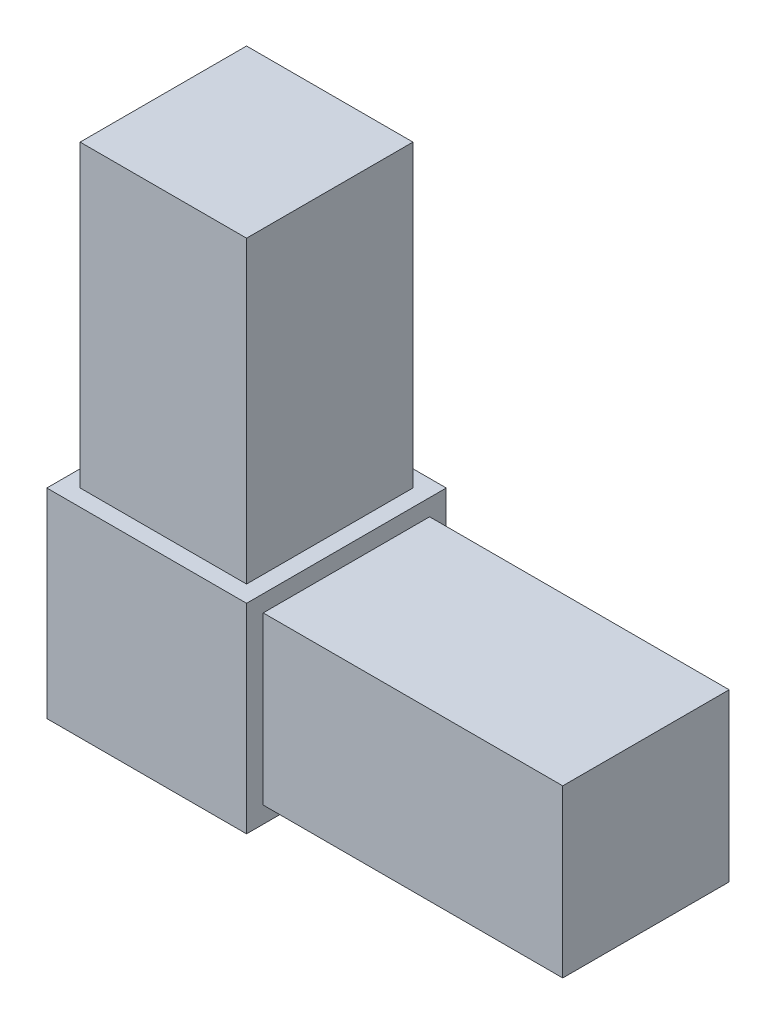
SolidWorks part; units mm, degrees
material "ABS"
ref_plane "Front Plane" through (0, 0, 0) normal (0, 0, 1) x (1, 0, 0)
ref_plane "Top Plane" through (0, 0, 0) normal (0, 1, 0) x (1, 0, 0)
ref_plane "Right Plane" through (0, 0, 0) normal (1, 0, 0) x (0, 0, -1)
sketch "Sketch1" plane through (0, 0, 0) normal (0, 0, 1) x (1, 0, 0)
  line L1 (9.525, -9.525) -> (-9.525, -9.525)
  line L2 (9.525, -9.525) -> (9.525, 9.525)
  line L3 (9.525, 9.525) -> (-9.525, 9.525)
  line L4 (-9.525, -9.525) -> (-9.525, 9.525)
  line L5 (9.525, -9.525) -> (-9.525, 9.525) construction
  line L6 (9.525, 9.525) -> (-9.525, -9.525) construction
  point P0 (0, 0)
  dimension "D1" = 19.05
extrude "Boss-Extrude1" add sketch "Sketch1" along normal blind 19.05
sketch "Sketch2" plane through (0, 9.525, 0) normal (0, 1, 0) x (1, 0, 0)
  line L0 (-9.525, 0) -> (9.525, -19.05) construction
  line L2 (-7.9375, -1.5875) -> (7.9375, -1.5875)
  line L3 (-7.9375, -1.5875) -> (-7.9375, -17.4625)
  line L4 (-7.9375, -17.4625) -> (7.9375, -17.4625)
  line L5 (7.9375, -1.5875) -> (7.9375, -17.4625)
  line L6 (-7.9375, -1.5875) -> (7.9375, -17.4625) construction
  line L7 (-7.9375, -17.4625) -> (7.9375, -1.5875) construction
  point P4 (0, -9.525)
  dimension "D1" = 15.875
extrude "Boss-Extrude2" add sketch "Sketch2" along normal blind 28.575
sketch "Sketch3" plane through (9.525, 0, 0) normal (1, 0, 0) x (0, 0, -1)
  line L0 (-19.05, 9.525) -> (0, -9.525) construction
  line L2 (-17.4625, -7.9375) -> (-1.5875, -7.9375)
  line L3 (-17.4625, -7.9375) -> (-17.4625, 7.9375)
  line L4 (-17.4625, 7.9375) -> (-1.5875, 7.9375)
  line L5 (-1.5875, -7.9375) -> (-1.5875, 7.9375)
  line L6 (-17.4625, -7.9375) -> (-1.5875, 7.9375) construction
  line L7 (-17.4625, 7.9375) -> (-1.5875, -7.9375) construction
  point P4 (-9.525, 0)
  dimension "D1" = 15.875
extrude "Boss-Extrude3" add sketch "Sketch3" along normal blind 28.575
equation "\"Height\"= 28in"
equation "\"Width\"= 28in"
equation "\"Depth\"= 20in"
equation "\"Plexi\"= .121in"
equation "\"MagnetThickness\"=3mm"
equation "\"MagnetDiameter\"=12mm"
equation "\"DoorPlexi\"= \"Plexi\""
equation "\"BasePlateThickness\"= 0.5in"
equation "\"BasePlateWidth\"= \"Width\"+8in-\"Plexi\""
equation "\"BasePlateDepth\"= \"Depth\"-\"Plexi\"-\"DoorPlexi\""
equation "\"Boxsize\"= .75in"
equation "\"Boxinner\"= .625in"
equation "\"CornerCube\"= 0.75in"
equation "\"FingerLength\"= 1.125in"
equation "\"Cutwidth\"= .016in"
equation "\"Earsize\"= 1in + \"Cutwidth\" /2"
equation "\"Slotsize\"= 1in - \"Cutwidth\" / 2"
equation "\"InnerWidth\"= \"Width\" - 2* \"Plexi\""
equation "\"InnerHeight\"= \"Height\" -2 * \"Plexi\""
equation "\"InnerDepth\"= \"Depth\" - 2*\"Plexi\""
equation "\"RearNumHoles\"= 7"
equation "\"RearHolesBorder\"= 2.2"
equation "\"RearHoleSpacing\"= (\"Width\" - 2*\"RearHolesBorder\") / (\"RearNumHoles\"-1)"
equation "\"RearBarLength\"= (\"InnerWidth\"-2*\"CornerCube\")"
equation "\"RearTopNumHoles\"= 6"
equation "\"RearTopHolesBorder\"= 2.5"
equation "\"RearTopHolesSpacing\"= (\"Width\" - 2*\"RearTopHolesBorder\") / (\"RearTopNumHoles\"-1)"
equation "\"SideTopNumHoles\"= 5"
equation "\"SideTopHoleOffset\"=\"CornerCube\"+\"FingerLength\"+\"Plexi\"+.5"
equation "\"SideTopHoleSpacing\"= (\"TopBarDepth\"-2*\"SideTopHoleOffset\") / (\"SideTopNumHoles\"-1)"
equation "\"SideHorizNumHoles\"= 6"
equation "\"SideHorizHoleBorder\"= 2.25"
equation "\"SideHorizHoleSpacing\"= (\"TopBarDepth\"-2*\"SideHorizHoleBorder\") / (\"SideHorizNumHoles\"-1)"
equation "\"SideVertBarLength\"=\"Height\"-\"BasePlateThickness\"-2*\"CornerCube\"-\"Plexi\""
equation "\"SideVertNumHoles\"= 6"
equation "\"SideVertHolesBorder\"= \"CornerCube\"+\"FingerLength\"+.9"
equation "\"SideVertHoleSpacing\"= (\"InnerHeight\" - 2*\"SideVertHolesBorder\") / (\"SideVertNumHoles\"-1)"
equation "\"RearSideVertNumHoles\"= 7"
equation "\"RearSideVertHolesBorder\"= 2.5"
equation "\"RearSideVertHoleSpacing\"= (\"InnerHeight\" - 2*\"RearSideVertHolesBorder\") / (\"RearSideVertNumHoles\"-1)"
equation "\"RivetDia\"= .228in"
equation "\"SlotDepth\"= \"Plexi\" + 0.75in + .005in"
equation "\"SideSlotWidth\"= \"Plexi\"+.005in"
equation "\"SidePanelVertSpacing\"= (\"Height\"-2*(1.75-\"Plexi\")) / 5"
equation "\"BottomPanelSideHoleSpacing\"= (\"InnerDepth\"-2*(1.75-\"Plexi\")) / 4"
equation "\"FrontDoorGap\"= .1in"
equation "\"TopDepth\"= \"Depth\"-\"DoorPlexi\"-\"FrontDoorGap\""
equation "\"TopBarDepth\"= \"Depth\"-\"DoorPlexi\"-\"Plexi\"-2*\"MagnetThickness\"-2*\"CornerCube\""
equation "\"D1@Boss-Extrude1\"=\"CornerCube\""
equation "\"D1@Sketch1\"=\"CornerCube\""
equation "\"D1@Boss-Extrude3\"=\"FingerLength\""
equation "\"D1@Boss-Extrude2\"=\"FingerLength\""
equation "\"FingerWidth\"= .625in"
equation "\"D1@Sketch3\"=\"FingerWidth\""
equation "\"D1@Sketch2\"=\"FingerWidth\""
